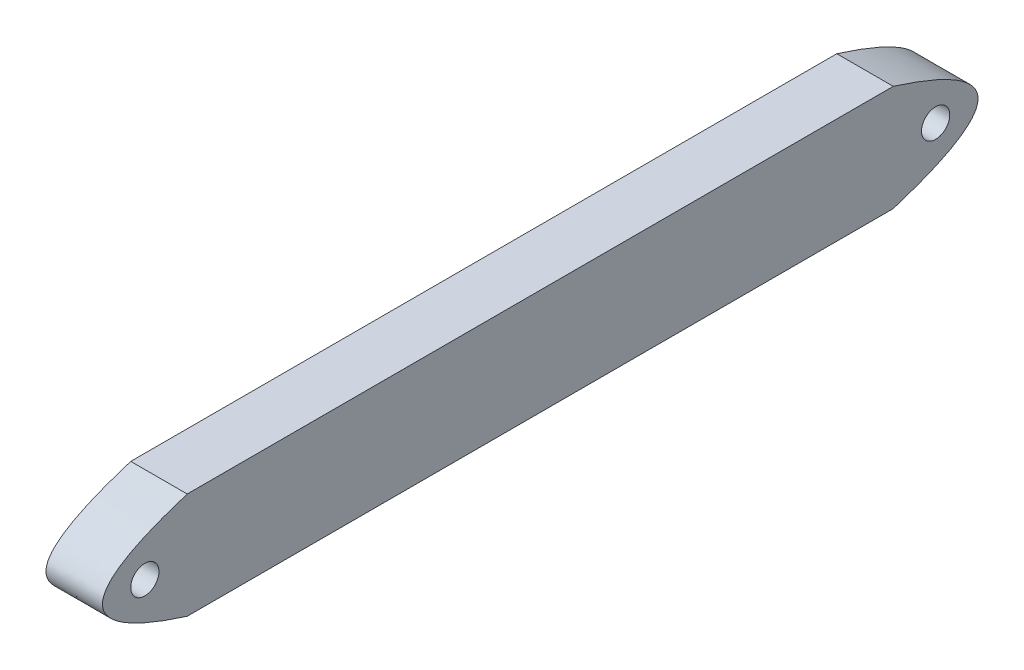
SolidWorks part; units mm, degrees
ref_plane "Front Plane" through (0, 0, 0) normal (0, 0, 1) x (1, 0, 0)
ref_plane "Top Plane" through (0, 0, 0) normal (0, 1, 0) x (1, 0, 0)
ref_plane "Right Plane" through (0, 0, 0) normal (1, 0, 0) x (0, 0, -1)
sketch "Sketch1" plane through (0, 0, 0) normal (1, 0, 0) x (0, 0, -1)
  line L0 (62.1484, -8.5017) -> (162.1484, -8.5017)
  line L1 (62.1484, -23.5017) -> (162.1484, -23.5017)
  circle A0 centre (56.1484, -16.0017) radius 2
  circle A1 centre (168.1484, -16.0017) radius 2
  spline S0 degree 2 poles (162.1484, -8.5017) (186.1484, -16.0017) (162.1484, -23.5017) knots 0 0 0 1 1 1
  spline S1 degree 2 poles (62.1484, -8.5017) (38.1484, -16.0017) (62.1484, -23.5017) knots 0 0 0 1 1 1
  point P10 (0, 0)
  dimension "D8" = 4
  dimension "D10" = 4
  dimension "D1" = 100
  dimension "D2" = 15
  dimension "D3" = 7.5
  dimension "D4" = 12
  dimension "D5" = 12
  dimension "D6" = 6
  dimension "D7" = 0
  dimension "D9" = 6
extrude "Boss-Extrude1" add sketch "Sketch1" along normal blind 8
